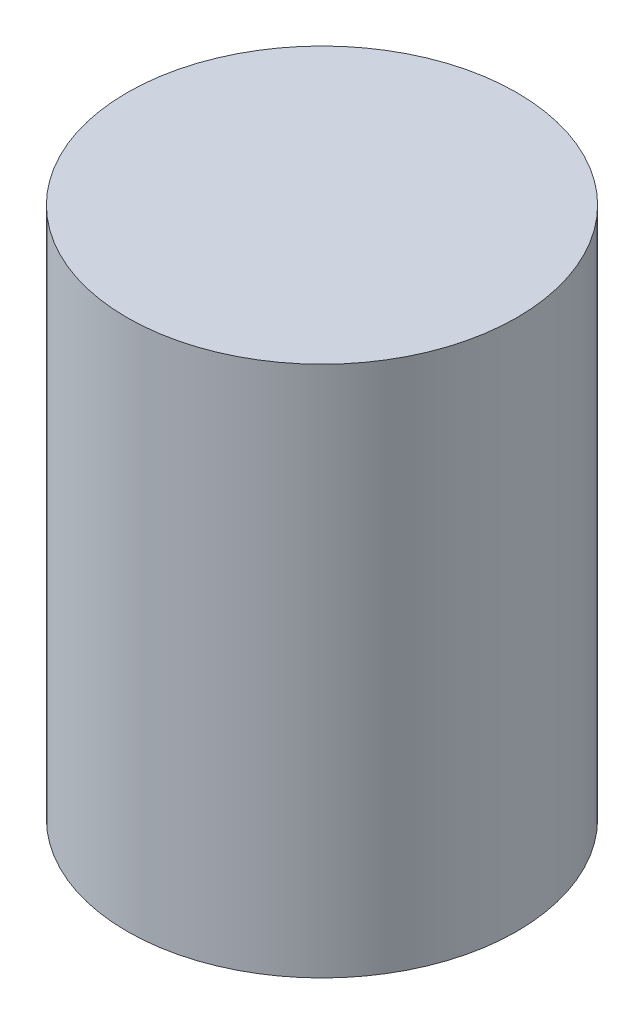
SolidWorks part; units mm, degrees
ref_plane "Plano frontal" through (0, 0, 0) normal (0, 0, 1) x (1, 0, 0)
ref_plane "Plano superior" through (0, 0, 0) normal (0, 1, 0) x (1, 0, 0)
ref_plane "Plano direito" through (0, 0, 0) normal (1, 0, 0) x (0, 0, -1)
sketch "Esboço2" plane through (0, 0, 0) normal (1, 0, 0) x (0, 0, -1)
  line L0 (0, 0) -> (2.75, 0)
  line L1 (2.75, 0) -> (2.75, 7.5)
  line L2 (2.75, 7.5) -> (0, 7.5)
  line L3 (0, 7.5) -> (0, 0)
  dimension "D1" = 7.5
  dimension "D2" = 2.75
revolve "Revolução3" add sketch "Esboço2" angle 360 about L1
